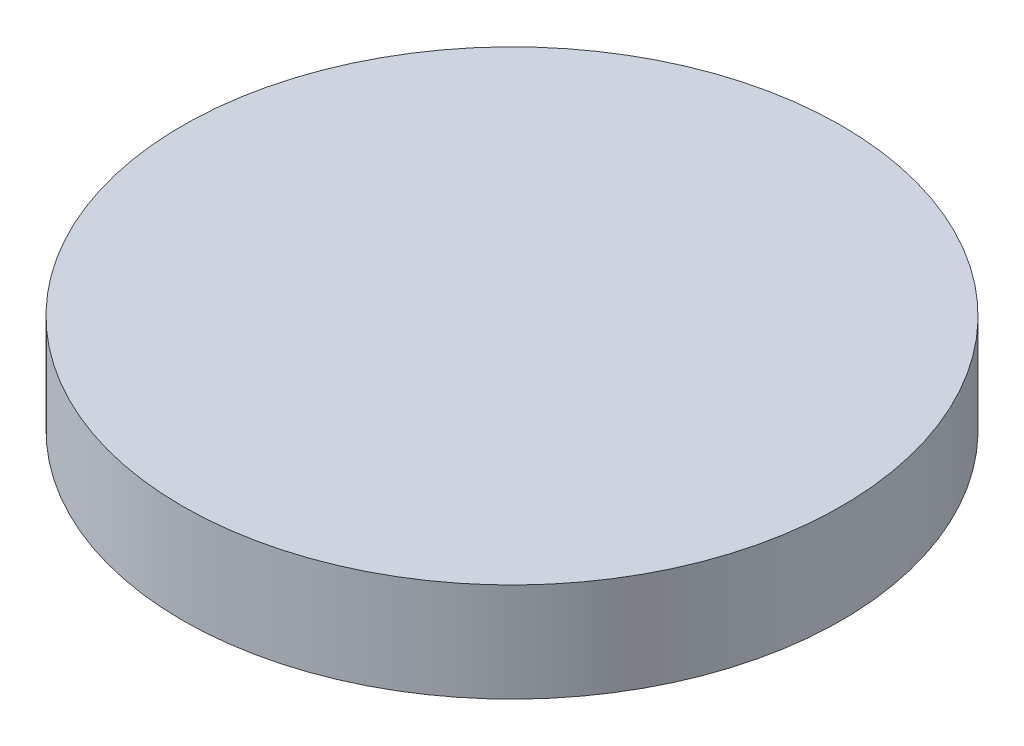
SolidWorks part; units mm, degrees
ref_plane "Front Plane" through (0, 0, 0) normal (0, 0, 1) x (1, 0, 0)
ref_plane "Top Plane" through (0, 0, 0) normal (0, 1, 0) x (1, 0, 0)
ref_plane "Right Plane" through (0, 0, 0) normal (1, 0, 0) x (0, 0, -1)
sketch "Sketch1" plane through (0, 0, 0) normal (0, 1, 0) x (1, 0, 0)
  circle A0 centre (0, 0) radius 25.4
extrude "Boss-Extrude2" add sketch "Sketch1" along normal blind 7.62 contours A0
sketch "Sketch4" plane through (0, 0, 0) normal (0, 1, 0) x (1, 0, 0)
  circle A0 centre (0, 0) radius 17.78 construction
  circle A1 centre (0, 17.78) radius 4.826
extrude "Cut-Extrude2" cut sketch "Sketch4" along normal blind 3.048
pattern_circular "CirPattern1" count 6 over 360 about axis through (0, 0, 0) along (0, 1, 0) of "Cut-Extrude2"
sketch "Sketch5" plane through (0, 0, 0) normal (0, 1, 0) x (1, 0, 0)
  circle A0 centre (0, 0) radius 4.826
sketch "Sketch6" plane through (0, 7.62, 0) normal (0, 1, 0) x (1, 0, 0)
  circle A0 centre (0, 0) radius 12.7
extrude "Boss-Extrude4" [suppressed] add sketch "Sketch6" along normal blind 41.91 draft 7
extrude "Cut-Extrude6" cut sketch "Sketch5" along normal blind 3.048
sketch "Sketch7" plane through (0, 0, 0) normal (0, -1, 0) x (1, 0, 0)
  line L0 (0, 17.78) -> (0, -0.3504) construction
  line L1 (0, -0.3504) -> (0, 0) construction
  line L2 (0, 0) -> (15.7022, 8.7148) construction
  line L3 (15.7022, 8.7148) -> (0, 17.78) construction
  line L4 (0, 17.78) -> (0, 0) construction
  line L5 (0, 0) -> (7.8511, 13.2474) construction
  circle A0 centre (0, 0) radius 8.89 construction
  circle A1 centre (4.5325, 7.6478) radius 0.7938
  circle A2 centre (4.3569, -7.7491) radius 0.7938
  circle A3 centre (-8.8894, 0.1014) radius 0.7937
  point P16 (0, 0)
  dimension "D1" = 3
extrude "Cut-Extrude7" cut sketch "Sketch7" against normal blind 1.5875
